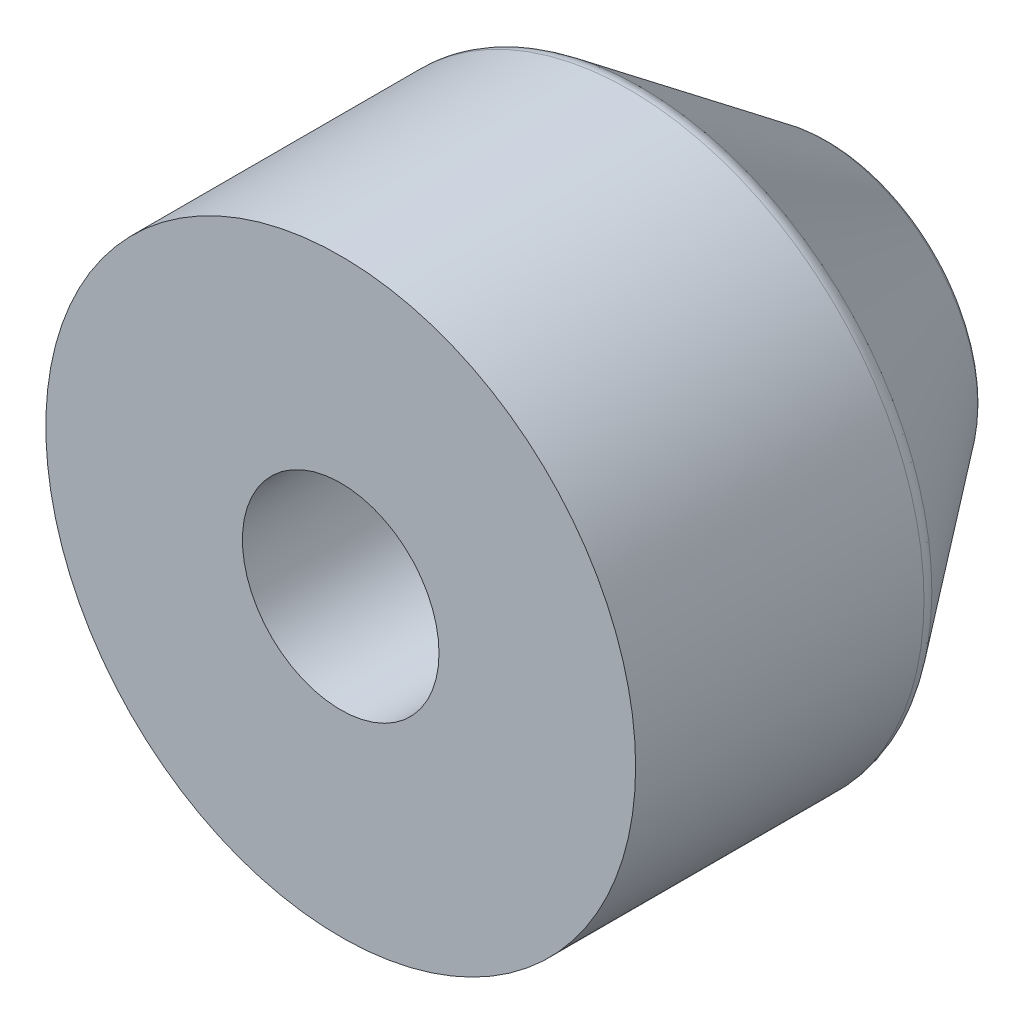
SolidWorks part; units mm, degrees
ref_plane "Plan de face" through (0, 0, 0) normal (0, 0, 1) x (1, 0, 0)
ref_plane "Plan de dessus" through (0, 0, 0) normal (0, 1, 0) x (1, 0, 0)
ref_plane "Plan de droite" through (0, 0, 0) normal (1, 0, 0) x (0, 0, -1)
sketch "Sketch1" plane through (0, 0, 0) normal (0, 1, 0) x (1, 0, 0)
  line L0 (0, 0) -> (0, 25.4) construction
  line L1 (5.08, 25.4) -> (5.08, 0)
  line L2 (5.08, 0) -> (15.24, 0)
  line L3 (15.24, 0) -> (15.24, 14.9013)
  line L4 (15.0368, 15.5109) -> (7.9248, 24.9936)
  line L5 (7.112, 25.4) -> (5.08, 25.4)
  arc A0 (15.24, 14.9013) -> (15.0368, 15.5109) centre (14.224, 14.9013) ccw
  arc A1 (7.9248, 24.9936) -> (7.112, 25.4) centre (7.112, 24.384) ccw
  point P10 (15.24, 15.24)
  point P13 (7.62, 25.4)
  dimension "D6" = 1.016
  dimension "D1" = 25.4
  dimension "D2" = 5.08
  dimension "D3" = 15.24
  dimension "D4" = 7.62
  dimension "D5" = 15.24
revolve "Revolve1" add sketch "Sketch1" angle 360 about L0
